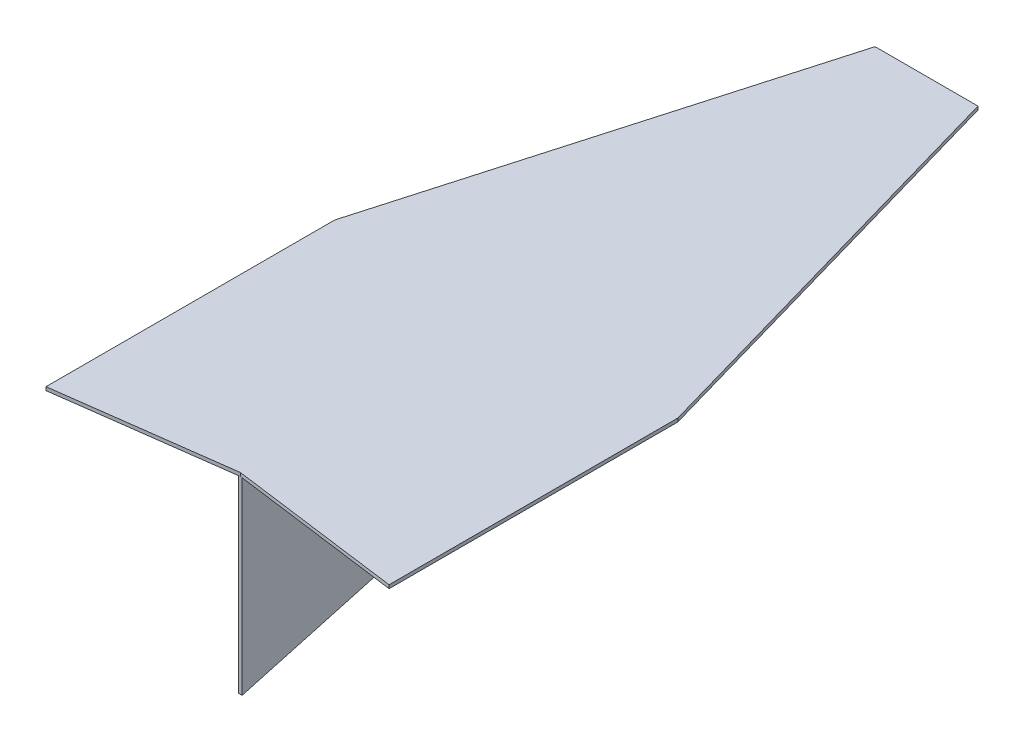
SolidWorks part; units mm, degrees
ref_plane "正面" through (0, 0, 0) normal (0, 0, 1) x (1, 0, 0)
ref_plane "平面" through (0, 0, 0) normal (0, 1, 0) x (1, 0, 0)
ref_plane "右側面" through (0, 0, 0) normal (1, 0, 0) x (0, 0, -1)
sketch "ｽｹｯﾁ1" plane through (0, 0, 0) normal (0, 1, 0) x (1, 0, 0)
  line L1 (-50, -105) -> (50, -105)
  line L2 (-50, -105) -> (-50, 105)
  line L3 (-50, 105) -> (50, 105)
  line L4 (50, -105) -> (50, 105)
  line L5 (-50, -105) -> (50, 105) construction
  line L6 (-50, 105) -> (50, -105) construction
  point P0 (0, 0)
  dimension "D1" = 210
  dimension "D2" = 100
extrude "ﾎﾞｽ - 押し出し1" add sketch "ｽｹｯﾁ1" along normal blind 1
sketch "ｽｹｯﾁ2" plane through (0, 1, 0) normal (0, 1, 0) x (1, 0, 0)
  line L0 (0, 0) -> (0, 105) construction
  line L1 (50, 105) -> (-50, 105) construction
  line L2 (0, 105) -> (60, 87.5)
  line L3 (-25, 70) -> (-15, 105)
  line L4 (60, 87.5) -> (25, 70)
  line L5 (25, 70) -> (75, -105)
  line L7 (-50, -105) -> (50, -105) construction
  line L8 (0, 0) -> (0, -105) construction
  line L10 (75, -105) -> (0, -95)
  line L11 (-75, -105) -> (0, -95)
  line L12 (60, 87.5) -> (-60, 87.5) construction
  line L13 (25, 70) -> (15, 105)
  line L17 (-25, 70) -> (-75, -105)
  line L18 (-60, 87.5) -> (-25, 70)
  line L19 (0, 105) -> (-60, 87.5)
  line L21 (50, -105) -> (-50, -105)
  line L22 (50, -105) -> (50, 105)
  line L23 (50, 105) -> (-50, 105)
  line L24 (-50, -105) -> (-50, 105)
  line L25 (50, -105) -> (-50, 105) construction
  line L26 (50, 105) -> (-50, -105) construction
  point P20 (0, 87.5)
  dimension "D1" = 35
  dimension "D2" = 75
  dimension "D3" = 17.5
  dimension "D4" = 25
  dimension "D5" = 120
  dimension "D6" = 10
extrude "ｶｯﾄ - 押し出し1" cut sketch "ｽｹｯﾁ2" against normal blind 1
sketch "ｽｹｯﾁ4" plane through (0, 0, 0) normal (1, 0, 0) x (0, 0, -1)
  line L0 (105, 0) -> (-95, -55)
  line L1 (-95, -55) -> (-95, 0)
  line L2 (105, 0) -> (105, 1) construction
  line L4 (105, 0) -> (-95, 0)
  dimension "D1" = 55
extrude "ﾎﾞｽ - 押し出し2" add sketch "ｽｹｯﾁ4" along normal blind 0.5 and the other way blind 0.5 contours L0 L4 L1
